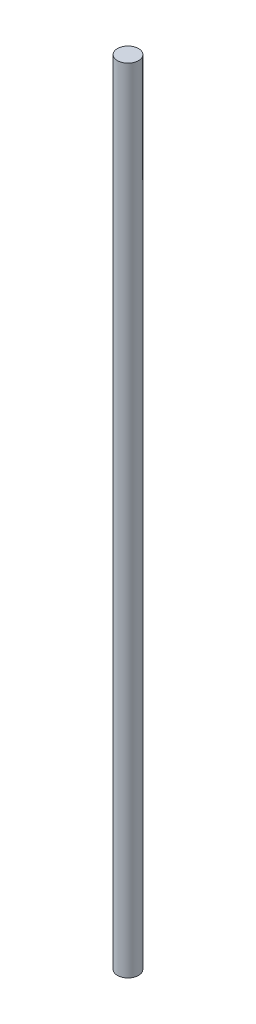
SolidWorks part; units mm, degrees
material "Aço inoxidável fundido"
ref_plane "Plano frontal" through (0, 0, 0) normal (0, 0, 1) x (1, 0, 0)
ref_plane "Plano superior" through (0, 0, 0) normal (0, 1, 0) x (1, 0, 0)
ref_plane "Plano direito" through (0, 0, 0) normal (1, 0, 0) x (0, 0, -1)
sketch "Esboço1" plane through (0, 0, 0) normal (0, 1, 0) x (1, 0, 0)
  circle A0 centre (0, 0) radius 4
  dimension "D1" = 8
extrude "Ressalto-extrusão1" add sketch "Esboço1" along normal mid plane 302
